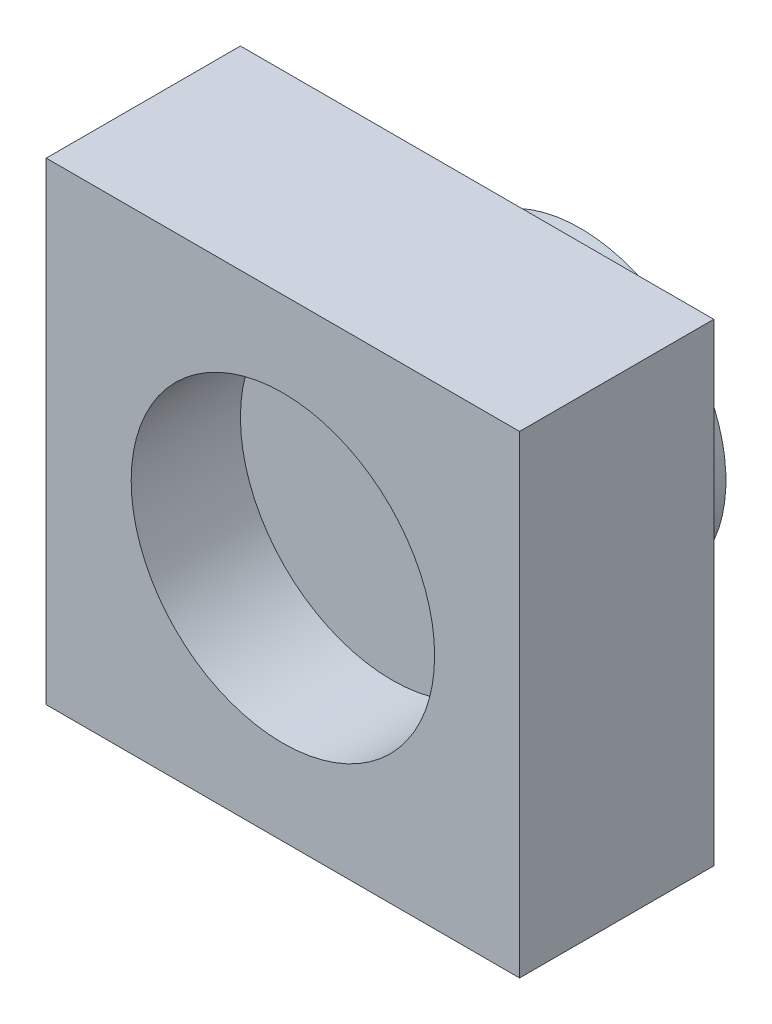
SolidWorks part; units mm, degrees
ref_plane "Спереди" through (0, 0, 0) normal (0, 0, 1) x (1, 0, 0)
ref_plane "Сверху" through (0, 0, 0) normal (0, 1, 0) x (1, 0, 0)
ref_plane "Справа" through (0, 0, 0) normal (1, 0, 0) x (0, 0, -1)
sketch "Эскиз1" plane through (0, 0, 0) normal (0, 0, 1) x (1, 0, 0)
  line L1 (3.9, 3.9) -> (-3.9, 3.9)
  line L2 (3.9, 3.9) -> (3.9, -3.9)
  line L3 (3.9, -3.9) -> (-3.9, -3.9)
  line L4 (-3.9, 3.9) -> (-3.9, -3.9)
  line L5 (3.9, 3.9) -> (-3.9, -3.9) construction
  line L6 (3.9, -3.9) -> (-3.9, 3.9) construction
  point P0 (0, 0)
  dimension "D1" = 7.8
  dimension "D2" = 7.8
extrude "Бобышка-Вытянуть1" add sketch "Эскиз1" along normal blind 3.2
sketch "Эскиз2" plane through (0, 0, 3.2) normal (0, 0, 1) x (1, 0, 0)
  circle A0 centre (0, 0) radius 2.5
extrude "Вырез-Вытянуть1" cut sketch "Эскиз2" against normal blind 1.8
sketch "Эскиз3" plane through (0, 0, 0) normal (0, 0, -1) x (-1, 0, 0)
  circle A0 centre (0, 0) radius 2.4
extrude "Бобышка-Вытянуть2" add sketch "Эскиз3" along normal blind 1.7
